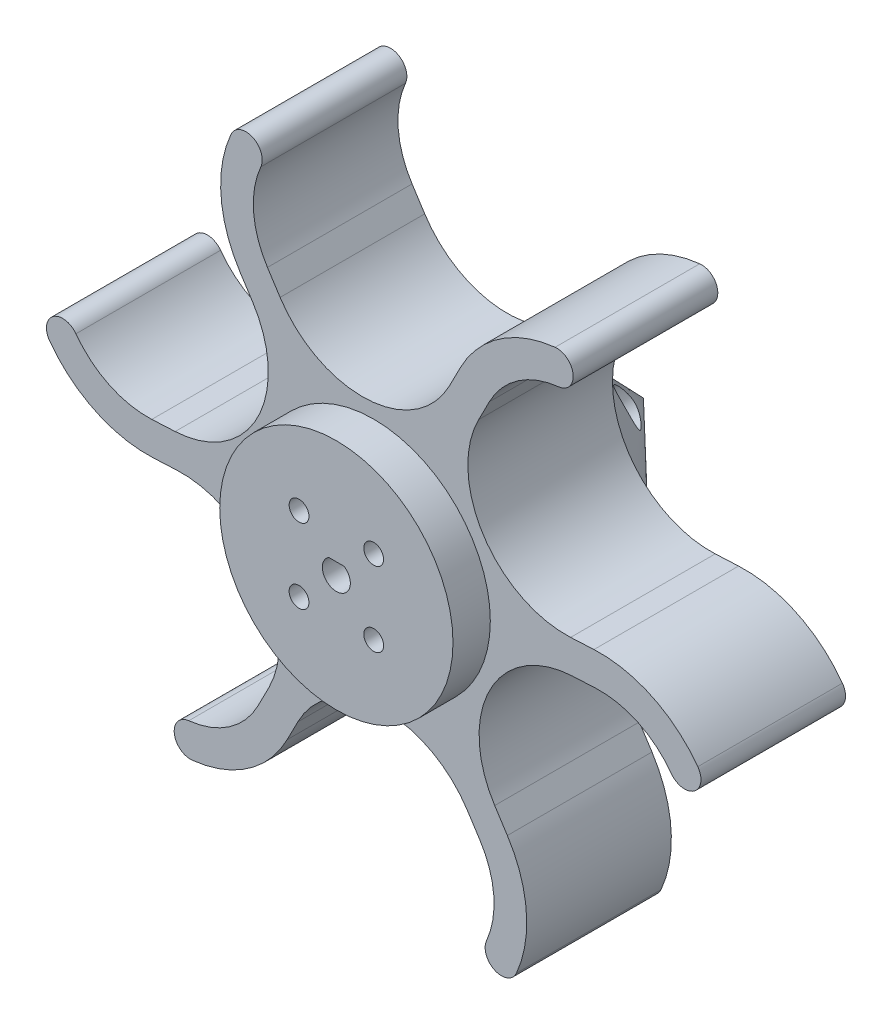
SolidWorks part; units mm, degrees
ref_plane "Front Plane" through (0, 0, 0) normal (0, 0, 1) x (1, 0, 0)
ref_plane "Top Plane" through (0, 0, 0) normal (0, 1, 0) x (1, 0, 0)
ref_plane "Right Plane" through (0, 0, 0) normal (1, 0, 0) x (0, 0, -1)
sketch "Sketch1" plane through (0, 0, 0) normal (0, 0, 1) x (1, 0, 0)
  line L0 (-33.6058, 45.6534) -> (-25.9397, 33.7658)
  line L1 (-30.6644, 47.5503) -> (-56.5119, -2.781) construction
  line L2 (-56.5119, -2.781) -> (-25.8475, -50.3313) construction
  line L3 (-25.8475, -50.3313) -> (30.6644, -47.5503) construction
  line L4 (30.6644, -47.5503) -> (56.5119, 2.781) construction
  line L5 (56.5119, 2.781) -> (25.8475, 50.3313) construction
  line L6 (25.8475, 50.3313) -> (-30.6644, 47.5503) construction
  line L7 (-27.723, 49.4471) -> (-20.0569, 37.5596)
  line L8 (22.7341, 51.9302) -> (16.2722, 39.3474)
  line L9 (28.961, 48.7324) -> (22.4991, 36.1496)
  line L10 (56.3399, 6.2768) -> (42.2119, 5.5815)
  line L11 (56.684, -0.7147) -> (42.556, -1.41)
  line L12 (33.6058, -45.6534) -> (25.9397, -33.7658)
  line L13 (27.723, -49.4471) -> (20.0569, -37.5596)
  line L14 (-22.7341, -51.9302) -> (-16.2722, -39.3474)
  line L15 (-28.961, -48.7324) -> (-22.4991, -36.1496)
  line L16 (-56.3399, -6.2768) -> (-42.2119, -5.5815)
  line L17 (-56.684, 0.7147) -> (-42.556, 1.41)
  circle A0 centre (41.1797, 26.5562) radius 21 construction
  circle A1 centre (43.5882, -22.3846) radius 21 construction
  circle A2 centre (2.4085, -48.9408) radius 21 construction
  circle A3 centre (-41.1797, -26.5562) radius 21 construction
  circle A4 centre (-43.5882, 22.3846) radius 21 construction
  circle A5 centre (-2.4085, 48.9408) radius 21 construction
  circle A6 centre (0, 0) radius 49 construction
  circle A7 centre (-30.6644, 47.5503) radius 3.5
  circle A8 centre (25.8475, 50.3313) radius 3.5
  circle A9 centre (56.5119, 2.781) radius 3.5
  circle A10 centre (30.6644, -47.5503) radius 3.5
  circle A11 centre (-25.8475, -50.3313) radius 3.5
  circle A12 centre (-56.5119, -2.781) radius 3.5
  arc A13 (-42.556, 1.41) -> (-25.9397, 33.7658) centre (-43.5882, 22.3846) ccw
  arc A14 (-20.0569, 37.5596) -> (16.2722, 39.3474) centre (-2.4085, 48.9408) ccw
  arc A15 (22.4991, 36.1496) -> (42.2119, 5.5815) centre (41.1797, 26.5562) ccw
  arc A16 (42.556, -1.41) -> (25.9397, -33.7658) centre (43.5882, -22.3846) ccw
  arc A17 (20.0569, -37.5596) -> (-16.2722, -39.3474) centre (2.4085, -48.9408) ccw
  arc A18 (-22.4991, -36.1496) -> (-42.2119, -5.5815) centre (-41.1797, -26.5562) ccw
  point P25 (0, 0)
  point P36 (0, 0)
  point P60 (0, 0)
  point P77 (0, 0)
  dimension "D2" = 42
  dimension "D4" = 7
  dimension "D1" = 6
  dimension "D3" = 6
  dimension "D5" = 6
  dimension "D6" = 6
extrude "Boss-Extrude1" add sketch "Sketch1" along normal blind 21 contours A18 L15 A11 L14 A17 L13 A10 L12 A16 L11 A9 L10 A15 L9 A8 L8 A14 L7 A7 L0 A13 L17 A12 L16 | A12 | A7 | A8 | A9 | A10 | A11
ref_plane "Plane1" through (0, 0, 0) normal (0.0492, -0.9988, 0) x (-0.9988, -0.0492, 0)
sketch "Sketch3" plane through (0, 0, 0) normal (0.0492, -0.9988, 0) x (-0.9988, -0.0492, 0)
  line L0 (0, 0) -> (-28, 0)
  line L1 (-28, 0) -> (0, 26.8135)
  line L2 (0, 26.8135) -> (0, 0)
  dimension "D1" = 28
revolve "Revolve1" add sketch "Sketch3" angle 360 about L2
sketch "Sketch4" plane through (0, 0, 21) normal (0, 0, 1) x (1, 0, 0)
  circle A0 centre (0, 0) radius 25
  dimension "D1" = 50
extrude "Boss-Extrude2" add sketch "Sketch4" along normal blind 18
sketch "Sketch5" plane through (0, 0, 39) normal (0, 0, 1) x (1, 0, 0)
  line L0 (-1.6583, 2.5) -> (1.6583, 2.5)
  arc A0 (-1.6583, 2.5) -> (1.6583, 2.5) centre (0, 0) ccw
  dimension "D1" = 6
  dimension "D2" = 2.5
extrude "Cut-Extrude2" cut sketch "Sketch5" against normal blind 20
ref_plane "Plane2" through (-1.2288, 24.9698, 0) normal (-0.0492, 0.9988, 0) x (0.9988, 0.0492, 0)
ref_plane "Plane5" through (1.2288, -24.9698, 0) normal (0.0492, -0.9988, 0) x (-0.9988, -0.0492, 0)
sketch "Sketch7" plane through (0, 0, 39) normal (0, 0, 1) x (1, 0, 0)
  line L0 (0, 12.9158) -> (0, -15.3556) construction
  line L1 (-12.6694, 0) -> (16.084, 0) construction
  circle A0 centre (-8, 8) radius 2.125
  circle A1 centre (8, 8) radius 2.125
  circle A2 centre (8, -8) radius 2.125
  circle A3 centre (-8, -8) radius 2.125
  dimension "D1" = 4.25
  dimension "D2" = 8
  dimension "D3" = 8
extrude "Cut-Extrude3" cut sketch "Sketch7" against normal through all
sketch "Sketch9" plane through (0, 0, 0) normal (0, 0, -1) x (-1, 0, 0)
  line L0 (0, 0) -> (24.2952, 0) construction
  line L1 (0, 0) -> (0, 21.4598) construction
  circle A1 centre (-8, 8) radius 2.125 construction
  circle A5 centre (-8, 8) radius 2.125 construction
  circle A8 centre (-8, 8) radius 4
  circle A10 centre (8, 8) radius 4
  circle A11 centre (8, -8) radius 4
  circle A12 centre (-8, -8) radius 4
  dimension "D1" = 8
extrude "Cut-Extrude4" cut sketch "Sketch9" against normal offset from surface 3 and the other way through all up to face at (-10.125, -8, 39)
sketch "Sketch10" plane through (0, 0, 21) normal (0, 0, 1) x (1, 0, 0)
  line L0 (-1.6583, 2.5) -> (1.6583, 2.5) construction
  line L1 (-1.6583, 2.5) -> (1.6583, 2.5)
  line L12 (-22.4991, -36.1496) -> (-28.961, -48.7324)
  line L13 (-22.7341, -51.9302) -> (-16.2722, -39.3474)
  line L14 (20.0569, -37.5596) -> (27.723, -49.4471)
  line L15 (33.6058, -45.6534) -> (25.9397, -33.7658)
  line L16 (42.556, -1.41) -> (56.684, -0.7147)
  line L17 (56.3399, 6.2768) -> (42.2119, 5.5815)
  line L18 (22.4991, 36.1496) -> (28.961, 48.7324)
  line L19 (22.7341, 51.9302) -> (16.2722, 39.3474)
  line L20 (-20.0569, 37.5596) -> (-27.723, 49.4471)
  line L21 (-33.6058, 45.6534) -> (-25.9397, 33.7658)
  line L22 (-42.556, 1.41) -> (-56.684, 0.7147)
  line L23 (-56.3399, -6.2768) -> (-42.2119, -5.5815)
  line L24 (-22.4991, -36.1496) -> (-28.961, -48.7324)
  line L25 (-22.7341, -51.9302) -> (-16.2722, -39.3474)
  line L26 (20.0569, -37.5596) -> (27.723, -49.4471)
  line L27 (33.6058, -45.6534) -> (25.9397, -33.7658)
  line L28 (42.556, -1.41) -> (56.684, -0.7147)
  line L29 (56.3399, 6.2768) -> (42.2119, 5.5815)
  line L30 (22.4991, 36.1496) -> (28.961, 48.7324)
  line L31 (22.7341, 51.9302) -> (16.2722, 39.3474)
  line L32 (-20.0569, 37.5596) -> (-27.723, 49.4471)
  line L33 (-33.6058, 45.6534) -> (-25.9397, 33.7658)
  line L34 (-42.556, 1.41) -> (-56.684, 0.7147)
  line L35 (-56.3399, -6.2768) -> (-42.2119, -5.5815)
  circle A0 centre (8, -8) radius 2.125 construction
  arc A1 (-1.6583, 2.5) -> (1.6583, 2.5) centre (0, 0) ccw construction
  circle A2 centre (-8, -8) radius 2.125 construction
  circle A3 centre (8, 8) radius 2.125 construction
  circle A4 centre (-8, 8) radius 2.125 construction
  circle A5 centre (8, -8) radius 2.125
  arc A6 (-1.6583, 2.5) -> (1.6583, 2.5) centre (0, 0) ccw
  circle A7 centre (-8, -8) radius 2.125
  circle A8 centre (8, 8) radius 2.125
  circle A9 centre (-8, 8) radius 2.125
  arc A12 (-22.4991, -36.1496) -> (-42.2119, -5.5815) centre (-41.1797, -26.5562) ccw
  arc A13 (-28.961, -48.7324) -> (-22.7341, -51.9302) centre (-25.8475, -50.3313) ccw
  arc A14 (20.0569, -37.5596) -> (-16.2722, -39.3474) centre (2.4085, -48.9408) ccw
  arc A15 (27.723, -49.4471) -> (33.6058, -45.6534) centre (30.6644, -47.5503) ccw
  arc A16 (42.556, -1.41) -> (25.9397, -33.7658) centre (43.5882, -22.3846) ccw
  arc A17 (56.684, -0.7147) -> (56.3399, 6.2768) centre (56.5119, 2.781) ccw
  arc A18 (22.4991, 36.1496) -> (42.2119, 5.5815) centre (41.1797, 26.5562) ccw
  arc A19 (28.961, 48.7324) -> (22.7341, 51.9302) centre (25.8475, 50.3313) ccw
  arc A20 (-20.0569, 37.5596) -> (16.2722, 39.3474) centre (-2.4085, 48.9408) ccw
  arc A21 (-27.723, 49.4471) -> (-33.6058, 45.6534) centre (-30.6644, 47.5503) ccw
  arc A22 (-42.556, 1.41) -> (-25.9397, 33.7658) centre (-43.5882, 22.3846) ccw
  arc A23 (-56.684, 0.7147) -> (-56.3399, -6.2768) centre (-56.5119, -2.781) ccw
  arc A24 (-22.4991, -36.1496) -> (-42.2119, -5.5815) centre (-41.1797, -26.5562) ccw
  arc A25 (-28.961, -48.7324) -> (-22.7341, -51.9302) centre (-25.8475, -50.3313) ccw
  arc A26 (20.0569, -37.5596) -> (-16.2722, -39.3474) centre (2.4085, -48.9408) ccw
  arc A27 (27.723, -49.4471) -> (33.6058, -45.6534) centre (30.6644, -47.5503) ccw
  arc A28 (42.556, -1.41) -> (25.9397, -33.7658) centre (43.5882, -22.3846) ccw
  arc A29 (56.684, -0.7147) -> (56.3399, 6.2768) centre (56.5119, 2.781) ccw
  arc A30 (22.4991, 36.1496) -> (42.2119, 5.5815) centre (41.1797, 26.5562) ccw
  arc A31 (28.961, 48.7324) -> (22.7341, 51.9302) centre (25.8475, 50.3313) ccw
  arc A32 (-20.0569, 37.5596) -> (16.2722, 39.3474) centre (-2.4085, 48.9408) ccw
  arc A33 (-27.723, 49.4471) -> (-33.6058, 45.6534) centre (-30.6644, 47.5503) ccw
  arc A34 (-42.556, 1.41) -> (-25.9397, 33.7658) centre (-43.5882, 22.3846) ccw
  arc A35 (-56.684, 0.7147) -> (-56.3399, -6.2768) centre (-56.5119, -2.781) ccw
  dimension "D1" = 0
extrude "Boss-Extrude3" add sketch "Sketch10" along normal blind 10
sketch "Sketch11" plane through (0, 0, 0) normal (0, 0, -1) x (-1, 0, 0)
  line L0 (-56.3399, 6.2768) -> (-42.2119, 5.5815) construction
  line L1 (-56.684, -0.7147) -> (-42.556, -1.41) construction
  line L2 (-56.3399, 6.2768) -> (-42.2119, 5.5815)
  line L3 (-56.684, -0.7147) -> (-42.556, -1.41)
  line L4 (-42.556, -1.41) -> (-47.556, -1.1639)
  line L5 (-42.2119, 5.5815) -> (-47.2119, 5.8276)
  line L6 (-42.2119, 5.5815) -> (-42.556, -1.41)
  circle A0 centre (-56.5119, 2.781) radius 3.5 construction
  arc A1 (-25.9397, -33.7658) -> (-42.556, -1.41) centre (-43.5882, -22.3846) ccw construction
  circle A2 centre (-56.5119, 2.781) radius 3.5
  arc A3 (-25.9397, -33.7658) -> (-42.556, -1.41) centre (-43.5882, -22.3846) ccw
  arc A4 (-47.556, -1.1639) -> (-63.8237, -8.9217) centre (-48.4899, -20.141) ccw
  arc A5 (-47.2119, 5.8276) -> (-69.4731, -4.7883) centre (-48.4899, -20.141) ccw
  circle A6 centre (-66.6484, -6.855) radius 3.5
  circle A7 centre (0, 0) radius 72 construction
  circle A8 centre (0, 0) radius 67
  dimension "D2" = 19
  dimension "D4" = 144
  dimension "D3" = 7
  dimension "D1" = 5
  dimension "D5" = 5
extrude "Boss-Extrude4" add sketch "Sketch11" against normal up to surface (31 mm away) contours A5 A8 A6 A4 L3 A2 | A8 A6 | A6 A8 | A2 A5 | L2 A5 A2 L3 L6 | A8 A5 A6
sketch "Sketch12" plane through (0, 0, 0) normal (0, 0, -1) x (-1, 0, 0)
  line L0 (-56.3399, 6.2768) -> (-42.2119, 5.5815) construction
  line L1 (-56.3399, 6.2768) -> (-42.2119, 5.5815)
  arc A0 (-59.9894, 3.1777) -> (-69.4731, -4.7883) centre (-48.4899, -20.141) ccw construction
  circle A1 centre (-56.5119, 2.781) radius 3.5 construction
  arc A2 (-59.9894, 3.1777) -> (-69.4731, -4.7883) centre (-48.4899, -20.141) ccw
  circle A3 centre (-56.5119, 2.781) radius 3.5
  arc A4 (-69.4731, -4.7883) -> (-42.2119, 5.5815) centre (-50.5685, -13.468) cw
  arc A5 (-47.2119, 5.8276) -> (-69.4731, -4.7883) centre (-48.4899, -20.141) ccw construction
  arc A6 (-47.2119, 5.8276) -> (-69.4731, -4.7883) centre (-48.4899, -20.141) ccw
  arc M1 (-56.3399, 6.2768) -> (-59.9894, 3.1777) centre (-56.5119, 2.781) ccw
  arc M2 (-59.9894, 3.1777) -> (-69.4731, -4.7883) centre (-48.4899, -20.141) ccw
  line M9 (-42.2119, 5.5815) -> (-56.3399, 6.2768)
extrude "Cut-Extrude5" cut sketch "Sketch12" against normal up to surface (31 mm away) contours A4 A3 M2 | A6 A3 M1 | A6 L1 A3 | A4 L1 M1 M9 up to face at (-5.875, 8, 31)
pattern_circular "CirPattern1" count 6 every 60 about axis through (0, 0, 0) along (0, 0, 1) of "Boss-Extrude4", "Cut-Extrude5"
